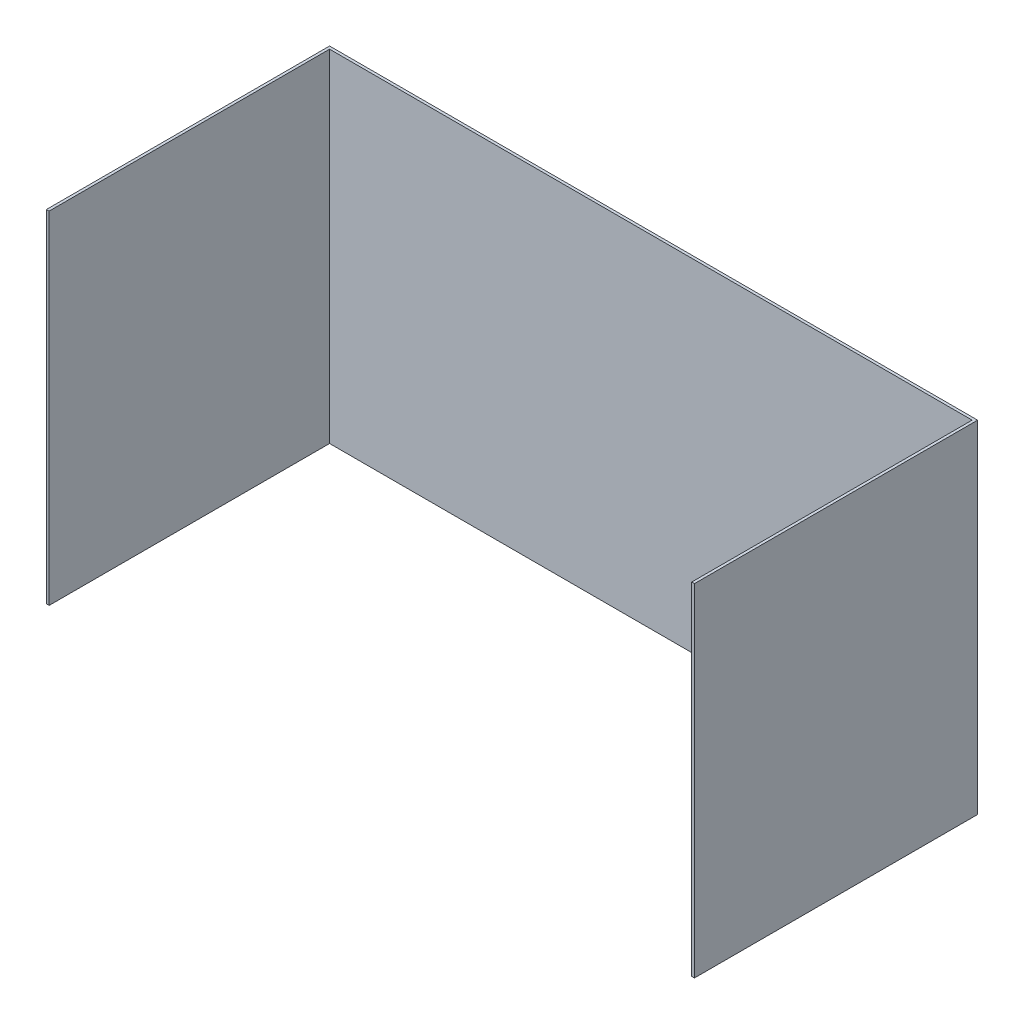
SolidWorks part; units mm, degrees
material "ABS PC"
ref_plane "Front Plane" through (0, 0, 0) normal (0, 0, 1) x (1, 0, 0)
ref_plane "Top Plane" through (0, 0, 0) normal (0, 1, 0) x (1, 0, 0)
ref_plane "Right Plane" through (0, 0, 0) normal (1, 0, 0) x (0, 0, -1)
sketch "Sketch1" plane through (0, 0, 0) normal (0, 0, 1) x (1, 0, 0)
  line L1 (-377.825, -199.136) -> (377.825, -199.136)
  line L2 (-377.825, -199.136) -> (-377.825, 199.136)
  line L3 (-377.825, 199.136) -> (377.825, 199.136)
  line L4 (377.825, -199.136) -> (377.825, 199.136)
  line L5 (-377.825, -199.136) -> (377.825, 199.136) construction
  line L6 (-377.825, 199.136) -> (377.825, -199.136) construction
  point P0 (0, 0)
  dimension "D1" = 398.272
  dimension "D2" = 755.65
extrude "Boss-Extrude1" add sketch "Sketch1" along normal blind 330.2
sketch "Sketch2" plane through (0, 0, 330.2) normal (0, 0, 1) x (1, 0, 0)
  line L0 (-377.825, -199.136) -> (377.825, -199.136) construction
  line L1 (-374.65, 199.136) -> (374.65, 199.136)
  line L2 (-374.65, 199.136) -> (-374.65, -199.136)
  line L3 (-374.65, -199.136) -> (374.65, -199.136)
  line L4 (374.65, 199.136) -> (374.65, -199.136)
  line L5 (-374.65, 199.136) -> (374.65, -199.136) construction
  line L6 (-374.65, -199.136) -> (374.65, 199.136) construction
  line L7 (-377.825, 199.136) -> (-377.825, -199.136) construction
  point P0 (0, 0)
  dimension "D1" = 3.175
extrude "Cut-Extrude1" cut sketch "Sketch2" against normal blind 327.025
